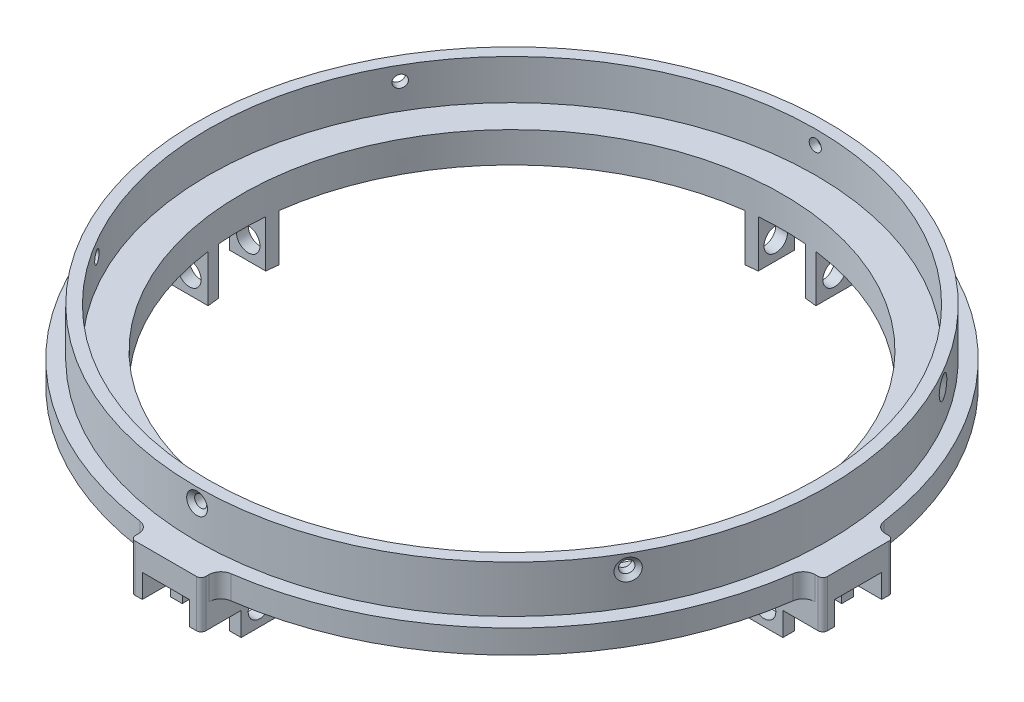
SolidWorks part; units mm, degrees
material "ASTM A36 Steel"
ref_plane "Front" through (0, 0, 0) normal (0, 0, 1) x (1, 0, 0)
ref_plane "Top" through (0, 0, 0) normal (0, 1, 0) x (1, 0, 0)
ref_plane "Right" through (0, 0, 0) normal (1, 0, 0) x (0, 0, -1)
sketch "Sketch1" plane through (0, 0, 0) normal (0, 1, 0) x (1, 0, 0)
  line L1 (-152.4, 152.4) -> (152.4, 152.4)
  line L2 (-152.4, 152.4) -> (-152.4, -152.4)
  line L3 (-152.4, -152.4) -> (152.4, -152.4)
  line L4 (152.4, 152.4) -> (152.4, -152.4)
  line L5 (-152.4, 152.4) -> (152.4, -152.4) construction
  line L6 (-152.4, -152.4) -> (152.4, 152.4) construction
  point P0 (0, 0)
  dimension "D1" = 304.8
  dimension "D2" = 304.8
extrude "Boss-Extrude1" add sketch "Sketch1" along normal blind 19.05
sketch "Sketch2" plane through (0, 19.05, 0) normal (0, 1, 0) x (1, 0, 0)
  circle A0 centre (0, 0) radius 81.915
  dimension "D1" = 163.83
extrude "Cut-Extrude1" cut sketch "Sketch2" against normal blind 10.795
sketch "Sketch3" plane through (0, 8.255, 0) normal (0, 1, 0) x (1, 0, 0)
  circle A0 centre (0, 0) radius 73.025
  dimension "D1" = 146.05
extrude "Cut-Extrude2" cut sketch "Sketch3" against normal up to next
sketch "Sketch4" plane through (0, 19.05, 0) normal (0, 1, 0) x (1, 0, 0)
  circle A0 centre (0, 0) radius 85.09
  dimension "D1" = 170.18
extrude "Cut-Extrude4" cut sketch "Sketch4" against normal blind 12.7 flip side to cut
hole_wizard "CSK for #4 Flat Head Machine Screw (100)1" positions "3DSketch6" profile "Sketch10" countersink size "#4" standard "ANSI Inch"
sketch3d "3DSketch6"
  point P0 (0.1296, 15.24, 85.0899)
  dimension "D1" = 3.81
sketch "Sketch10" plane through (0.1296, 15.24, 85.0899) normal (0, 1, 0) x (1, 0, -0.0015)
  line L0 (0, 0) -> (0, 197.0349)
  line L1 (0, 197.0349) -> (1.6319, 197.0349)
  line L2 (1.6319, 197.0349) -> (1.6319, 1.0284)
  line L3 (1.6319, 1.0284) -> (2.8575, 0)
  line L5 (2.8575, 0) -> (0, 0)
  line L6 (-1.6319, 1.0284) -> (-2.8575, 0) construction
  line L11 (0, -6.35) -> (0, 107.95) construction
  dimension "Thru Hole Dia." = 3.2639
  dimension "Thru Hole Depth" = 197.0349
  dimension "Near C'Sink Dia." = 5.715
  dimension "Near C'Sink Angle" = 100
pattern_circular "CirPattern1" count 6 over 360 about axis through (0, 19.05, 0) along (0, 1, 0) of "CSK for #4 Flat Head Machine Screw (100)1"
sketch "Sketch11" plane through (0, 6.35, 0) normal (0, 1, 0) x (1, 0, 0)
  line L0 (-91.1949, 9.525) -> (-92.075, 9.525)
  line L1 (0, 0) -> (0, 88.9) construction
  line L2 (-93.345, 8.255) -> (-93.345, -8.255)
  line L3 (-92.075, -9.525) -> (-91.1949, -9.525)
  line L4 (9.525, 91.1949) -> (9.525, 92.075)
  line L5 (8.255, 93.345) -> (-8.255, 93.345)
  line L6 (-9.525, 92.075) -> (-9.525, 91.1949)
  line L7 (0, 0) -> (88.9, 0) construction
  line L8 (88.9, 0) -> (93.345, 0) construction
  line L9 (-9.525, -91.1949) -> (-9.525, -92.075)
  line L10 (-8.255, -93.345) -> (8.255, -93.345)
  line L11 (9.525, -92.075) -> (9.525, -91.1949)
  line L12 (0, 0) -> (0, -88.9) construction
  line L13 (0, -88.9) -> (0, -93.345) construction
  line L14 (91.1949, -9.525) -> (92.075, -9.525)
  line L15 (93.345, -8.255) -> (93.345, 8.255)
  line L16 (0, 88.9) -> (0, 93.345) construction
  line L17 (92.075, 9.525) -> (91.1949, 9.525)
  line L18 (0, 0) -> (-88.9, 0) construction
  line L19 (-88.9, 0) -> (-93.345, 0) construction
  circle A0 centre (0, 0) radius 85.09 construction
  arc A1 (-91.1949, 9.525) -> (-88.0503, 12.2621) centre (-91.1949, 12.7) ccw
  arc A2 (-92.075, 9.525) -> (-93.345, 8.255) centre (-92.075, 8.255) ccw
  arc A3 (-93.345, -8.255) -> (-92.075, -9.525) centre (-92.075, -8.255) ccw
  arc A4 (-91.1949, -9.525) -> (-88.0503, -12.2621) centre (-91.1949, -12.7) cw
  arc A5 (9.525, 91.1949) -> (12.2621, 88.0503) centre (12.7, 91.1949) ccw
  arc A6 (8.255, -93.345) -> (9.525, -92.075) centre (8.255, -92.075) ccw
  arc A7 (9.525, 92.075) -> (8.255, 93.345) centre (8.255, 92.075) ccw
  arc A8 (-8.255, 93.345) -> (-9.525, 92.075) centre (-8.255, 92.075) ccw
  arc A9 (-9.525, 91.1949) -> (-12.2621, 88.0503) centre (-12.7, 91.1949) cw
  circle A10 centre (0, 0) radius 73.025 construction
  arc A11 (9.525, -91.1949) -> (12.2621, -88.0503) centre (12.7, -91.1949) cw
  arc A12 (-9.525, -91.1949) -> (-12.2621, -88.0503) centre (-12.7, -91.1949) ccw
  arc A13 (-9.525, -92.075) -> (-8.255, -93.345) centre (-8.255, -92.075) ccw
  arc A14 (91.1949, -9.525) -> (88.0503, -12.2621) centre (91.1949, -12.7) ccw
  arc A15 (92.075, -9.525) -> (93.345, -8.255) centre (92.075, -8.255) ccw
  arc A16 (93.345, 8.255) -> (92.075, 9.525) centre (92.075, 8.255) ccw
  circle A17 centre (0, 0) radius 88.9
  arc A18 (91.1949, 9.525) -> (88.0503, 12.2621) centre (91.1949, 12.7) cw
  circle A22 centre (0, 0) radius 79.375 construction
  circle A23 centre (0, 0) radius 98.425 construction
  point P1 (0, 73.025)
  point P50 (0, 0)
  point P69 (0, 0)
  point P72 (0, 0)
  dimension "D1" = 3.175
  dimension "D4" = 1.27
  dimension "D7" = 177.8
  dimension "D8" = 4
  dimension "D5" = 158.75
  dimension "D9" = 19.05
  dimension "D2" = 0.8801
  dimension "D3" = 20.32
  dimension "D6" = 4
extrude "Cut-Extrude7" cut sketch "Sketch11" against normal blind 19.05
sketch "Sketch16" plane through (0, 0, 0) normal (0, 1, 0) x (1, 0, 0)
  line L1 (152.4, -152.4) -> (-152.4, -152.4) construction
  line L4 (-152.4, -152.4) -> (-152.4, 152.4) construction
  point P0 (0, 0)
  dimension "D1" = 304.8
  dimension "D2" = 304.8
  dimension "D3" = 152.4
  dimension "D4" = 152.4
sketch "Sketch18" plane through (0, 0, 0) normal (0, -1, 0) x (1, 0, 0)
  line L0 (0, 93.345) -> (0, 0) construction
  line L1 (-8.255, 93.345) -> (8.255, 93.345) construction
  line L2 (6.35, 72.7484) -> (-6.35, 72.7484) construction
  line L3 (6.35, 72.7484) -> (6.35, 93.345)
  line L4 (6.35, 93.345) -> (-6.35, 93.345) construction
  line L5 (-6.35, 72.7484) -> (-6.35, 93.345)
  line L6 (6.35, 72.7484) -> (-6.35, 93.345) construction
  line L7 (6.35, 93.345) -> (-6.35, 72.7484) construction
  line L8 (-9.525, 92.075) -> (-9.525, 72.4011)
  line L9 (-6.35, 93.345) -> (-8.255, 93.345)
  line L10 (9.525, 92.075) -> (9.525, 72.4011)
  line L11 (6.35, 93.345) -> (8.255, 93.345)
  line L12 (72.7484, -6.35) -> (93.345, -6.35)
  line L13 (72.7484, 6.35) -> (93.345, 6.35)
  line L14 (92.075, 9.525) -> (72.4011, 9.525)
  line L15 (93.345, 6.35) -> (93.345, 8.255)
  line L16 (92.075, -9.525) -> (72.4011, -9.525)
  line L17 (93.345, -6.35) -> (93.345, -8.255)
  line L18 (93.345, 0) -> (0, 0) construction
  line L19 (72.7484, -6.35) -> (72.7484, 6.35) construction
  line L20 (93.345, -6.35) -> (93.345, 6.35) construction
  line L21 (72.7484, -6.35) -> (93.345, 6.35) construction
  line L22 (93.345, -6.35) -> (72.7484, 6.35) construction
  line L23 (-6.35, -72.7484) -> (-6.35, -93.345)
  line L24 (6.35, -72.7484) -> (6.35, -93.345)
  line L25 (9.525, -92.075) -> (9.525, -72.4011)
  line L26 (6.35, -93.345) -> (8.255, -93.345)
  line L27 (-9.525, -92.075) -> (-9.525, -72.4011)
  line L28 (-6.35, -93.345) -> (-8.255, -93.345)
  line L29 (0, -93.345) -> (0, 0) construction
  line L30 (-6.35, -72.7484) -> (6.35, -72.7484) construction
  line L31 (-6.35, -93.345) -> (6.35, -93.345) construction
  line L32 (-6.35, -72.7484) -> (6.35, -93.345) construction
  line L33 (-6.35, -93.345) -> (6.35, -72.7484) construction
  line L34 (-72.7484, 6.35) -> (-93.345, 6.35)
  line L35 (-72.7484, -6.35) -> (-93.345, -6.35)
  line L36 (-92.075, -9.525) -> (-72.4011, -9.525)
  line L37 (-93.345, -6.35) -> (-93.345, -8.255)
  line L38 (-92.075, 9.525) -> (-72.4011, 9.525)
  line L39 (-93.345, 6.35) -> (-93.345, 8.255)
  line L40 (-93.345, 0) -> (0, 0) construction
  line L41 (-72.7484, 6.35) -> (-72.7484, -6.35) construction
  line L42 (-93.345, 6.35) -> (-93.345, -6.35) construction
  line L43 (-72.7484, 6.35) -> (-93.345, -6.35) construction
  line L44 (-93.345, 6.35) -> (-72.7484, -6.35) construction
  arc A0 (-6.35, 72.7484) -> (-9.525, 72.4011) centre (0, 0) ccw
  circle A1 centre (0, 0) radius 73.025 construction
  arc A2 (9.525, 72.4011) -> (6.35, 72.7484) centre (0, 0) ccw
  arc A3 (-9.525, 92.075) -> (-8.255, 93.345) centre (-8.255, 92.075) cw
  arc A4 (9.525, 92.075) -> (8.255, 93.345) centre (8.255, 92.075) ccw
  arc A5 (72.7484, 6.35) -> (72.4011, 9.525) centre (0, 0) ccw
  arc A6 (72.4011, -9.525) -> (72.7484, -6.35) centre (0, 0) ccw
  arc A7 (92.075, 9.525) -> (93.345, 8.255) centre (92.075, 8.255) cw
  arc A8 (92.075, -9.525) -> (93.345, -8.255) centre (92.075, -8.255) ccw
  arc A9 (6.35, -72.7484) -> (9.525, -72.4011) centre (0, 0) ccw
  arc A10 (-9.525, -72.4011) -> (-6.35, -72.7484) centre (0, 0) ccw
  arc A11 (9.525, -92.075) -> (8.255, -93.345) centre (8.255, -92.075) cw
  arc A12 (-9.525, -92.075) -> (-8.255, -93.345) centre (-8.255, -92.075) ccw
  arc A13 (-72.7484, -6.35) -> (-72.4011, -9.525) centre (0, 0) ccw
  arc A14 (-72.4011, 9.525) -> (-72.7484, 6.35) centre (0, 0) ccw
  arc A15 (-92.075, -9.525) -> (-93.345, -8.255) centre (-92.075, -8.255) cw
  arc A16 (-92.075, 9.525) -> (-93.345, 8.255) centre (-92.075, 8.255) ccw
  point P3 (0, 83.0467)
  point P25 (83.0467, 0)
  point P39 (0, -83.0467)
  point P53 (-83.0467, 0)
  point P66 (0, 0)
  dimension "D2" = 4
  dimension "D3" = 1.27
  dimension "D1" = 12.7
extrude "Boss-Extrude2" add sketch "Sketch18" along normal blind 12.7
sketch "Sketch19" plane through (9.525, 0, 0) normal (1, 0, 0) x (0, 0, -1)
  line L0 (-96.1332, -6.35) -> (-82.5611, -6.35)
  line L1 (-72.4011, 0) -> (-91.1949, 0) construction
  line L2 (-82.5611, -7.62) -> (-82.5611, -12.7)
  line L3 (-82.5611, -12.7) -> (-70.8041, -12.7)
  line L4 (-72.4011, -12.7) -> (-92.075, -12.7) construction
  line L5 (-82.5611, -7.62) -> (-82.5611, -6.35)
  line L7 (-70.8041, -12.7) -> (-70.8041, -20.3968)
  line L8 (-70.8041, -20.3968) -> (-96.1332, -20.3968)
  line L9 (-96.1332, -20.3968) -> (-96.1332, -6.35)
  line L10 (-72.4011, -12.7) -> (-72.4011, 0) construction
  arc A0 (-82.5611, -7.62) -> (-72.4011, -7.62) centre (-77.4811, -7.62) ccw construction
  dimension "D2" = 10.16
  dimension "D1" = 6.35
extrude "Cut-Extrude12" cut sketch "Sketch19" against normal blind 19.05
pattern_circular "CirPattern6" count 4 over 360 about axis through (0, 0, 0) along (0, 1, 0) of "Cut-Extrude12"
sketch "Sketch20" plane through (9.525, 0, 0) normal (1, 0, 0) x (0, 0, -1)
  line L0 (-72.4011, -12.7) -> (-72.4011, 0) construction
  line L1 (-72.4011, -12.7) -> (-82.5611, -12.7) construction
  circle A0 centre (-77.4811, -7.62) radius 5.08 construction
  circle A1 centre (-77.4811, -7.62) radius 3.175
  dimension "D1" = 10.16
  dimension "D2" = 6.35
extrude "Cut-Extrude13" cut sketch "Sketch20" against normal blind 19.05
pattern_circular "CirPattern7" count 4 over 360 about axis through (0, 19.05, 0) along (0, 1, 0) of "Cut-Extrude13"
